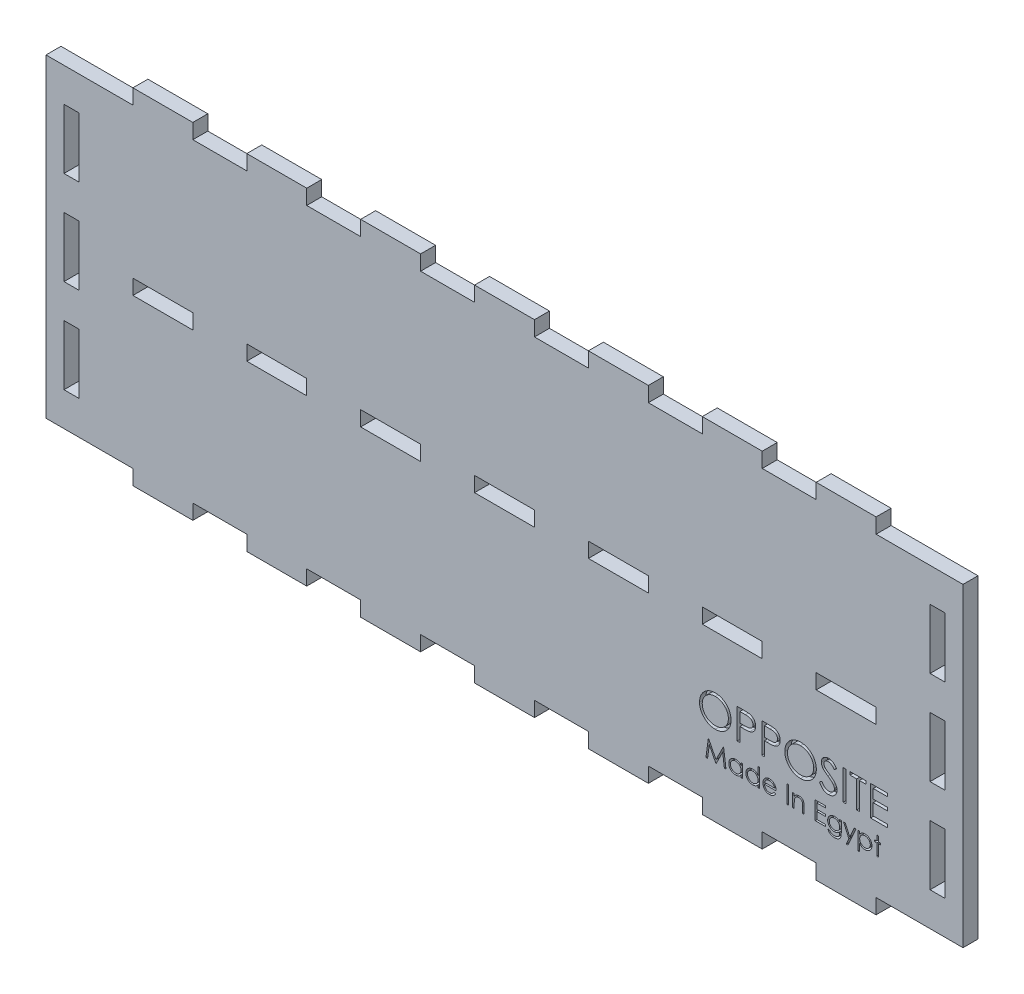
SolidWorks part; units mm, degrees
material "Beech"
ref_plane "Front" through (0, 0, 0) normal (0, 0, 1) x (1, 0, 0)
ref_plane "Top" through (0, 0, 0) normal (0, 1, 0) x (1, 0, 0)
ref_plane "Right" through (0, 0, 0) normal (1, 0, 0) x (0, 0, -1)
sketch "Sketch1" plane through (0, 0, 0) normal (0, 0, 1) x (1, 0, 0)
  line L0 (-76.5, 26.25) -> (-62, 26.25)
  line L1 (-76.5, -28.75) -> (76.5, -28.75) construction
  line L2 (-76.5, -28.75) -> (-76.5, 28.75) construction
  line L3 (-76.5, 28.75) -> (76.5, 28.75) construction
  line L4 (76.5, -28.75) -> (76.5, 28.75) construction
  line L5 (-76.5, -28.75) -> (76.5, 28.75) construction
  line L6 (-76.5, 28.75) -> (76.5, -28.75) construction
  line L7 (-73.5, -26.25) -> (73.5, -26.25) construction
  line L8 (-73.5, -26.25) -> (-73.5, 26.25) construction
  line L9 (-73.5, 26.25) -> (73.5, 26.25) construction
  line L10 (73.5, -26.25) -> (73.5, 26.25) construction
  line L11 (-73.5, -26.25) -> (73.5, 26.25) construction
  line L12 (-73.5, 26.25) -> (73.5, -26.25) construction
  line L13 (-62, 26.25) -> (-62, 28.75)
  line L14 (-62, 28.75) -> (-52, 28.75)
  line L15 (-52, 28.75) -> (-52, 26.25)
  line L16 (-52, 26.25) -> (-43, 26.25)
  line L17 (-43, 26.25) -> (-43, 28.75)
  line L18 (-43, 28.75) -> (-33, 28.75)
  line L19 (-33, 28.75) -> (-33, 26.25)
  line L20 (-33, 26.25) -> (-24, 26.25)
  line L21 (-24, 26.25) -> (-24, 28.75)
  line L22 (-24, 28.75) -> (-14, 28.75)
  line L23 (-14, 28.75) -> (-14, 26.25)
  line L24 (-14, 26.25) -> (-5, 26.25)
  line L25 (-5, 26.25) -> (-5, 28.75)
  line L26 (-5, 28.75) -> (5, 28.75)
  line L27 (0, 7.4006) -> (0, -7.3436) construction
  line L28 (10.0896, 0) -> (-10.0896, 0) construction
  line L29 (5, 26.25) -> (5, 28.75)
  line L30 (14, 26.25) -> (5, 26.25)
  line L31 (14, 28.75) -> (14, 26.25)
  line L32 (24, 28.75) -> (14, 28.75)
  line L33 (24, 26.25) -> (24, 28.75)
  line L34 (33, 26.25) -> (24, 26.25)
  line L35 (33, 28.75) -> (33, 26.25)
  line L36 (43, 28.75) -> (33, 28.75)
  line L37 (43, 26.25) -> (43, 28.75)
  line L38 (52, 26.25) -> (43, 26.25)
  line L39 (52, 28.75) -> (52, 26.25)
  line L40 (62, 28.75) -> (52, 28.75)
  line L41 (62, 26.25) -> (62, 28.75)
  line L42 (76.5, 26.25) -> (62, 26.25)
  line L43 (76.5, -26.25) -> (62, -26.25)
  line L44 (62, -26.25) -> (62, -28.75)
  line L45 (62, -28.75) -> (52, -28.75)
  line L46 (52, -28.75) -> (52, -26.25)
  line L47 (52, -26.25) -> (43, -26.25)
  line L48 (43, -26.25) -> (43, -28.75)
  line L49 (43, -28.75) -> (33, -28.75)
  line L50 (33, -28.75) -> (33, -26.25)
  line L51 (33, -26.25) -> (24, -26.25)
  line L52 (24, -26.25) -> (24, -28.75)
  line L53 (24, -28.75) -> (14, -28.75)
  line L54 (14, -28.75) -> (14, -26.25)
  line L55 (14, -26.25) -> (5, -26.25)
  line L56 (5, -26.25) -> (5, -28.75)
  line L57 (-5, -28.75) -> (5, -28.75)
  line L58 (-5, -26.25) -> (-5, -28.75)
  line L59 (-14, -26.25) -> (-5, -26.25)
  line L60 (-14, -28.75) -> (-14, -26.25)
  line L61 (-24, -28.75) -> (-14, -28.75)
  line L62 (-24, -26.25) -> (-24, -28.75)
  line L63 (-33, -26.25) -> (-24, -26.25)
  line L64 (-33, -28.75) -> (-33, -26.25)
  line L65 (-43, -28.75) -> (-33, -28.75)
  line L66 (-43, -26.25) -> (-43, -28.75)
  line L67 (-52, -26.25) -> (-43, -26.25)
  line L68 (-52, -28.75) -> (-52, -26.25)
  line L69 (-62, -28.75) -> (-52, -28.75)
  line L70 (-62, -26.25) -> (-62, -28.75)
  line L71 (-76.5, -26.25) -> (-62, -26.25)
  line L72 (76.5, 26.25) -> (76.5, -26.25)
  line L73 (-76.5, 26.25) -> (-76.5, -26.25)
  line L74 (-73.5, 10.625) -> (-71, 10.625)
  line L75 (73.5, 20.625) -> (71, 20.625)
  line L76 (73.5, 20.625) -> (73.5, 10.625)
  line L77 (73.5, 10.625) -> (71, 10.625)
  line L78 (71, 20.625) -> (71, 10.625)
  line L79 (73.5, 20.625) -> (71, 10.625) construction
  line L80 (73.5, 10.625) -> (71, 20.625) construction
  line L81 (-71, 20.625) -> (-71, 10.625)
  line L82 (-73.5, 20.625) -> (-71, 20.625)
  line L83 (-73.5, 20.625) -> (-73.5, 10.625)
  line L84 (73.5, 5) -> (73.5, -5)
  line L85 (73.5, 5) -> (71, 5)
  line L86 (71, 5) -> (71, -5)
  line L87 (73.5, -5) -> (71, -5)
  line L88 (-73.5, -5) -> (-71, -5)
  line L89 (-71, 5) -> (-71, -5)
  line L90 (-73.5, 5) -> (-71, 5)
  line L91 (-73.5, 5) -> (-73.5, -5)
  line L92 (73.5, -10.625) -> (73.5, -20.625)
  line L93 (73.5, -10.625) -> (71, -10.625)
  line L94 (71, -10.625) -> (71, -20.625)
  line L95 (73.5, -20.625) -> (71, -20.625)
  line L96 (-73.5, -20.625) -> (-71, -20.625)
  line L97 (-71, -10.625) -> (-71, -20.625)
  line L98 (-73.5, -10.625) -> (-71, -10.625)
  line L99 (-73.5, -10.625) -> (-73.5, -20.625)
  line L100 (-43, -1.25) -> (-43, 1.25)
  line L101 (-62, -1.25) -> (-52, -1.25)
  line L102 (-62, -1.25) -> (-62, 1.25)
  line L103 (-62, 1.25) -> (-52, 1.25)
  line L104 (-52, -1.25) -> (-52, 1.25)
  line L105 (-62, -1.25) -> (-52, 1.25) construction
  line L106 (-62, 1.25) -> (-52, -1.25) construction
  line L107 (-43, -1.25) -> (-33, -1.25)
  line L108 (-33, -1.25) -> (-33, 1.25)
  line L109 (-43, 1.25) -> (-33, 1.25)
  line L110 (-24, -1.25) -> (-24, 1.25)
  line L111 (-24, -1.25) -> (-14, -1.25)
  line L112 (-14, -1.25) -> (-14, 1.25)
  line L113 (-24, 1.25) -> (-14, 1.25)
  line L114 (-5, -1.25) -> (-5, 1.25)
  line L115 (-5, -1.25) -> (5, -1.25)
  line L116 (5, -1.25) -> (5, 1.25)
  line L117 (-5, 1.25) -> (5, 1.25)
  line L118 (14, -1.25) -> (14, 1.25)
  line L119 (14, -1.25) -> (24, -1.25)
  line L120 (24, -1.25) -> (24, 1.25)
  line L121 (14, 1.25) -> (24, 1.25)
  line L122 (33, -1.25) -> (33, 1.25)
  line L123 (33, -1.25) -> (43, -1.25)
  line L124 (43, -1.25) -> (43, 1.25)
  line L125 (33, 1.25) -> (43, 1.25)
  line L126 (52, -1.25) -> (52, 1.25)
  line L127 (52, -1.25) -> (62, -1.25)
  line L128 (62, -1.25) -> (62, 1.25)
  line L129 (52, 1.25) -> (62, 1.25)
  point P0 (0, 0)
  point P6 (0, 0)
  point P31 (0, 28.75)
  point P80 (72.25, 15.625)
  point P81 (72.25, 20.625)
  point P86 (-72.25, 10.625)
  point P87 (-57, 0)
  dimension "D1" = 57.5
  dimension "D2" = 153
  dimension "D3" = 2.5
  dimension "D4" = 3
  dimension "D5" = 10
  dimension "D6" = 9
  dimension "D7" = 11.5
  dimension "D8" = 14.5
  dimension "D9" = 14.5
  dimension "D10" = 14.5
  dimension "D11" = 14.5
  dimension "D12" = 5.625
  dimension "D14" = 5.625
  dimension "D15" = 9
  dimension "D17" = 9
  dimension "D13" = 3
  dimension "D16" = 7
extrude "Boss-Extrude1" add sketch "Sketch1" along normal blind 2.5
sketch "Sketch2" plane through (0, 0, 2.5) normal (0, 0, 1) x (1, 0, 0)
  line L0 (29.1314, -15.2213) -> (67.1645, -15.2213) construction
  line L1 (29.1314, -20.2213) -> (67.1645, -20.2213) construction
  text T0 "OPPOSITE" font "Century Gothic" height 5
  text T1 "Made In Egypt" font "Century Gothic" height 3
  point P4 (0, 0)
  point P6 (59.7615, -20.5885)
  point P7 (61.6122, -21.2363)
  point P8 (0, 0)
  point P9 (60.2242, -18.4601)
  point P10 (0, 0)
  point P11 (30.8897, -15.5914)
  point P12 (28.8538, -16.0541)
  point P13 (25.9852, -15.9616)
  point P14 (67.1645, -15.4064)
  point P15 (32.7404, -15.3138)
  point P16 (29.1314, -15.2213)
  dimension "D1" = 5
extrude "Cut-Extrude1" cut sketch "Sketch2" against normal blind 1
